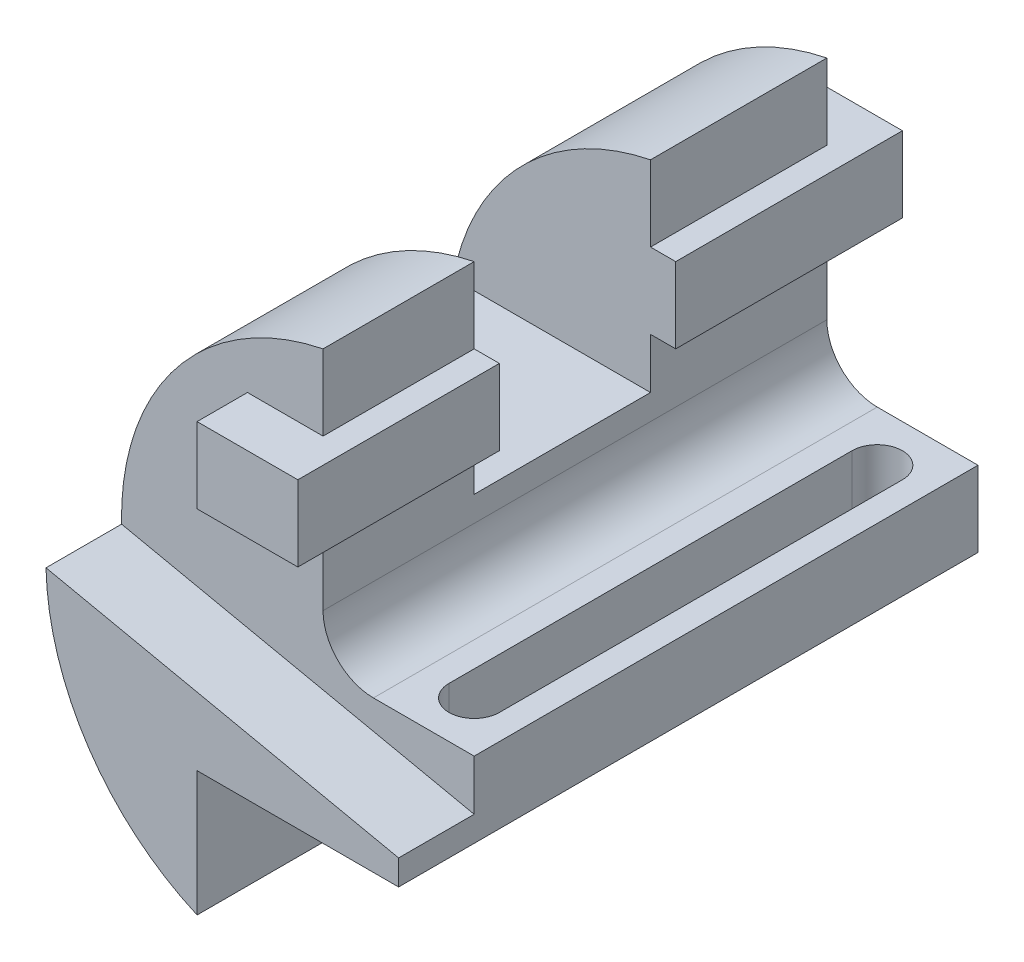
SolidWorks part; units mm, degrees
material "1060 Alloy"
ref_plane "Front Plane" through (0, 0, 0) normal (0, 0, 1) x (1, 0, 0)
ref_plane "Top Plane" through (0, 0, 0) normal (0, 1, 0) x (1, 0, 0)
ref_plane "Right Plane" through (0, 0, 0) normal (1, 0, 0) x (0, 0, -1)
sketch "Sketch1" plane through (0, 0, 0) normal (0, 0, 1) x (1, 0, 0)
  line L0 (0, 0) -> (-40, 0)
  line L1 (-40, 0) -> (-40, -24.8156)
  line L2 (0, 0) -> (0, 15)
  line L3 (0, 15) -> (-20, 15)
  line L4 (-30, 25) -> (-30, 70)
  arc A0 (-30, 70) -> (-40, -24.8156) centre (-20, 21.0102) ccw
  arc A1 (-20, 15) -> (-30, 25) centre (-20, 25) cw
  point P10 (-30, 15)
  dimension "D4" = 10
  dimension "D6" = 50
  dimension "D7" = 10
  dimension "D1" = 40
  dimension "D2" = 15
  dimension "D3" = 55
  dimension "D5" = 30
extrude "Boss-Extrude1" add sketch "Sketch1" along normal blind 115
sketch "Sketch2" plane through (0, 0, 115) normal (0, 0, 1) x (1, 0, 0)
  line L0 (0, 5) -> (-69.9871, 19.8762)
  line L1 (0, 0) -> (0, 15) construction
  line L2 (-40, 0) -> (0, 0) construction
  line L8 (0, 0) -> (0, 15)
  line L9 (0, 15) -> (-20, 15)
  line L10 (-30, 25) -> (-30, 70)
  line L11 (-40, -24.8156) -> (-40, 0)
  line L12 (-40, 0) -> (0, 0)
  line L13 (0, 5) -> (0, 15)
  line L14 (0, 15) -> (-20, 15)
  line L15 (-30, 25) -> (-30, 70)
  arc A2 (-30, 25) -> (-20, 15) centre (-20, 25) ccw
  arc A3 (-30, 70) -> (-40, -24.8156) centre (-20, 21.0102) ccw
  arc A4 (-30, 25) -> (-20, 15) centre (-20, 25) ccw
  arc A5 (-30, 70) -> (-69.9871, 19.8762) centre (-20, 21.0102) ccw
  dimension "D1" = 5
  dimension "D2" = 78
  dimension "D3" = 0
extrude "Cut-Extrude1" cut sketch "Sketch2" against normal blind 15
sketch "Sketch3" plane through (0, 0, 0) normal (0, 0, -1) x (-1, 0, 0)
  line L0 (30, 25) -> (30, 70) construction
  line L1 (25, 55) -> (45, 55)
  line L2 (25, 55) -> (25, 40)
  line L3 (25, 40) -> (45, 40)
  line L4 (45, 55) -> (45, 40)
  dimension "D1" = 15
  dimension "D2" = 15
  dimension "D3" = 5
  dimension "D4" = 20
extrude "Boss-Extrude2" add sketch "Sketch3" against normal offset from surface 5 and the other way blind 10 up to face at (-31.3027, -0.8636, 115)
sketch "Sketch4" plane through (-30, 0, 0) normal (1, 0, 0) x (0, 0, -1)
  line L0 (-100, 70) -> (0, 70) construction
  line L1 (-70, 70) -> (-35, 70)
  line L2 (-70, 70) -> (-70, 30)
  line L3 (-70, 30) -> (-35, 30)
  line L4 (-35, 70) -> (-35, 30)
  line L5 (-100, 55) -> (-100, 70) construction
  line L6 (-100, 40) -> (0, 40) construction
  dimension "D1" = 35
  dimension "D2" = 30
  dimension "D3" = 10
extrude "Cut-Extrude2" cut sketch "Sketch4" against normal through all both and the other way through all
sketch "Sketch5" plane through (0, 15, 0) normal (0, 1, 0) x (1, 0, 0)
  line L0 (-10, -10) -> (-10, -90) construction
  line L1 (-5, -10) -> (-5, -90)
  line L2 (-15, -10) -> (-15, -90)
  line L3 (0, 0) -> (-20, 0) construction
  line L5 (0, -100) -> (0, 0) construction
  arc A0 (-5, -10) -> (-15, -10) centre (-10, -10) ccw
  arc A1 (-15, -90) -> (-5, -90) centre (-10, -90) ccw
  point P2 (-10, -50)
  dimension "D1" = 80
  dimension "D2" = 10
  dimension "D3" = 10
  dimension "D4" = 10
extrude "Cut-Extrude3" cut sketch "Sketch5" against normal through all both
equation "\"a\"= 50"
equation "\"b\"= 55"
equation "\"c\"= 35"
